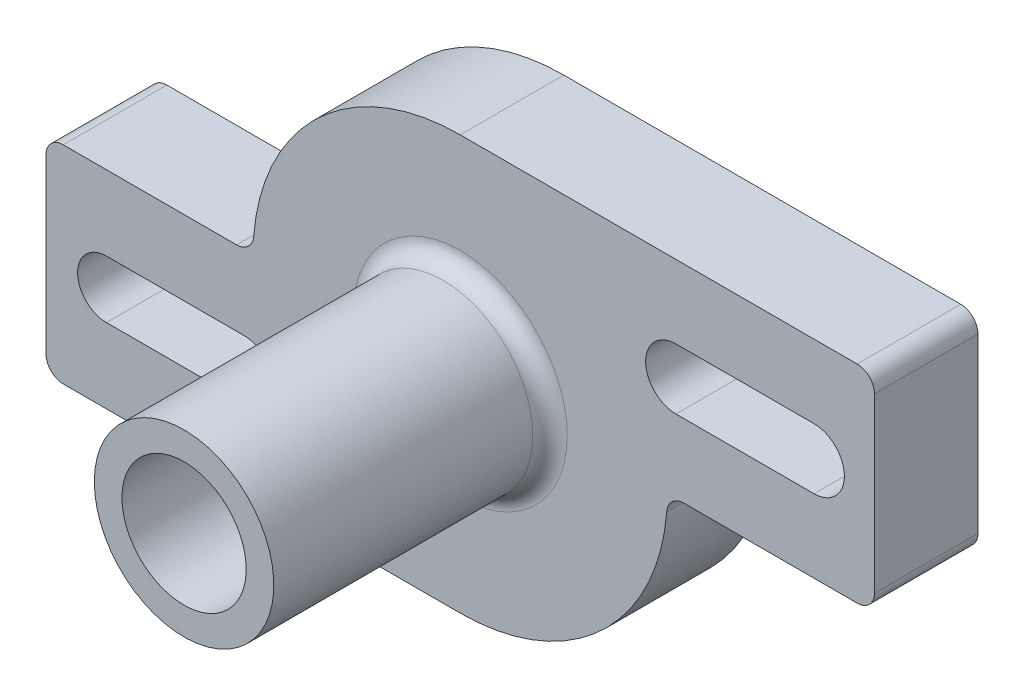
SolidWorks part; units mm, degrees
ref_plane "Front Plane" through (0, 0, 0) normal (0, 0, 1) x (1, 0, 0)
ref_plane "Top Plane" through (0, 0, 0) normal (0, 1, 0) x (1, 0, 0)
ref_plane "Right Plane" through (0, 0, 0) normal (1, 0, 0) x (0, 0, -1)
sketch "Sketch1" plane through (0, 0, 0) normal (0, 0, 1) x (1, 0, 0)
  line L0 (-37.5398, 91.3957) -> (-41.5398, 91.3957) construction
  line L3 (-37.5398, 90.5167) -> (-41.5398, 90.5167)
  line L4 (-47.7898, 94.3957) -> (-35.7898, 94.3957)
  line L5 (-59.7898, 82.3957) -> (-47.7898, 82.3957)
  line L6 (-53.7898, 88.3957) -> (-59.7898, 88.3957)
  line L7 (-41.7898, 88.3957) -> (-35.7898, 88.3957)
  line L8 (-59.7898, 88.3957) -> (-59.7898, 82.3957)
  line L9 (-35.7898, 94.3957) -> (-35.7898, 88.3957)
  line L10 (-37.5398, 92.2746) -> (-41.5398, 92.2746)
  line L11 (-58.0398, 85.3957) -> (-54.0398, 85.3957) construction
  line L12 (-58.0398, 86.2297) -> (-54.0398, 86.2297)
  line L13 (-58.0398, 84.5616) -> (-54.0398, 84.5616)
  arc A1 (-37.5398, 90.5167) -> (-37.5398, 92.2746) centre (-37.5398, 91.3957) ccw
  arc A2 (-47.7898, 94.3957) -> (-53.7898, 88.3957) centre (-47.7898, 88.3957) ccw
  arc A3 (-47.7898, 82.3957) -> (-41.7898, 88.3957) centre (-47.7898, 88.3957) ccw
  arc A4 (-41.5398, 92.2746) -> (-41.5398, 90.5167) centre (-41.5398, 91.3957) ccw
  arc A5 (-58.0398, 86.2297) -> (-58.0398, 84.5616) centre (-58.0398, 85.3957) ccw
  arc A6 (-54.0398, 84.5616) -> (-54.0398, 86.2297) centre (-54.0398, 85.3957) ccw
  point P7 (-39.5398, 91.3957)
  point P16 (-56.0398, 85.3957)
  dimension "D3" = 6
  dimension "D1" = 12
  dimension "D2" = 12
  dimension "D4" = 6
  dimension "D5" = 6
  dimension "D6" = 4
  dimension "D7" = 4
  dimension "D8" = 6.25
  dimension "D9" = 6.25
  dimension "D10" = 3
  dimension "D11" = 3
extrude "Boss-Extrude1" add sketch "Sketch1" along normal blind 3
sketch "Sketch2" plane through (0, 0, 3) normal (0, 0, -1) x (-1, 0, 0)
  circle A0 centre (47.7898, 88.3957) radius 2.6
  dimension "D1" = 5.2
extrude "Boss-Extrude2" add sketch "Sketch2" against normal blind 8
fillet "Fillet1" radius 0.5 7 edges at (-59.7898, 82.3957, 1.5) (-59.7898, 88.3957, 1.5) (-53.7898, 88.3957, 1.5) (-41.7898, 88.3957, 1.5) (-35.7898, 88.3957, 1.5) (-35.7898, 94.3957, 1.5) (-45.1898, 88.3957, 3)
hole_wizard "CBORE for M3 Hex Socket Thin Head Cap Screw1" positions "Sketch4" profile "Sketch3" counterbore size "M3" standard "DIN" end condition through all
sketch "Sketch4" plane through (0, 0, 0) normal (0, 0, -1) x (-1, 0, 0)
  point P0 (47.7898, 88.3957)
sketch "Sketch3" plane through (-47.7898, 88.3957, 0) normal (1, 0, 0) x (0, 1, 0)
  line L0 (0, 0) -> (0, 11)
  line L1 (0, 11) -> (1.8, 11)
  line L3 (1.8, 11) -> (1.8, 2.4)
  line L4 (1.8, 2.4) -> (3.25, 2.4)
  line L5 (3.25, 2.4) -> (3.25, 0)
  line L7 (3.25, 0) -> (0, 0)
  line L11 (0, -6.35) -> (0, 107.95) construction
  dimension "Thru Hole Dia." = 3.6
  dimension "Thru Hole Depth" = 11
  dimension "C'Bore Dia." = 6.5
  dimension "C'Bore Depth" = 2.4
